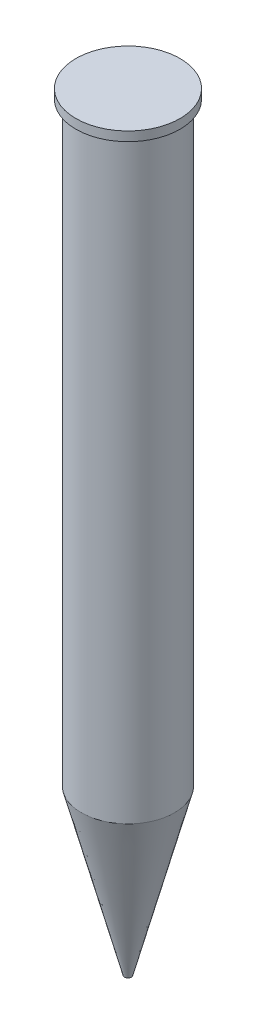
SolidWorks part; units mm, degrees
material "2014 Alloy"
ref_plane "Front Plane" through (0, 0, 0) normal (0, 0, 1) x (1, 0, 0)
ref_plane "Top Plane" through (0, 0, 0) normal (0, 1, 0) x (1, 0, 0)
ref_plane "Right Plane" through (0, 0, 0) normal (1, 0, 0) x (0, 0, -1)
sketch "Sketch1" plane through (0, 0, 0) normal (0, 1, 0) x (1, 0, 0)
  circle A0 centre (0, 0) radius 63.5
extrude "Boss-Extrude1" add sketch "Sketch1" along normal blind 812.8
sketch "Sketch2" plane through (0, 812.8, 0) normal (0, 1, 0) x (1, 0, 0)
  circle A0 centre (0, 0) radius 71.1286
extrude "Boss-Extrude2" add sketch "Sketch2" along normal blind 12.7
sketch "Sketch5" plane through (0, 0, 0) normal (1, 0, 0) x (0, 0, -1)
  line L0 (-63.5, 0) -> (0, 0)
  line L1 (-63.5, 0) -> (63.5, 0) construction
  line L2 (0, 0) -> (0, -223.941)
  line L3 (0, -223.941) -> (-4.6894, -223.941)
  line L4 (-4.6894, -223.941) -> (-63.5, 0)
revolve "Revolve2" add sketch "Sketch5" angle 360 about L2
